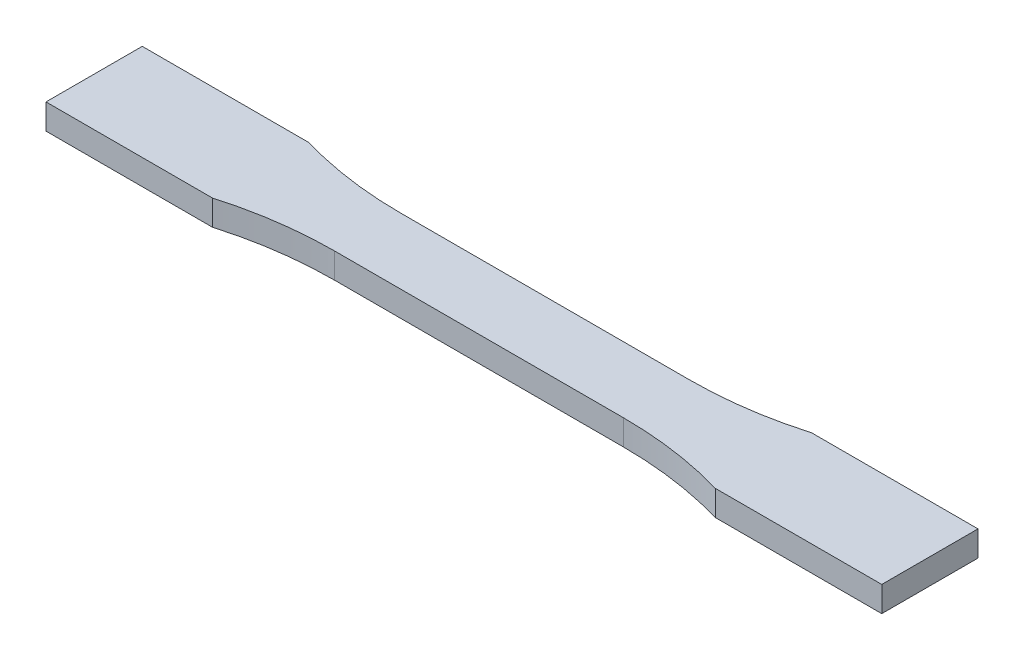
SolidWorks part; units mm, degrees
ref_plane "정면" through (0, 0, 0) normal (0, 0, 1) x (1, 0, 0)
ref_plane "윗면" through (0, 0, 0) normal (0, 1, 0) x (1, 0, 0)
ref_plane "우측면" through (0, 0, 0) normal (1, 0, 0) x (0, 0, -1)
sketch "스케치1" plane through (0, 0, 0) normal (0, 1, 0) x (1, 0, 0)
  line L0 (0, 23.452) -> (0, -24.9244) construction
  line L1 (-28.5, 6.5) -> (28.5, 6.5)
  line L2 (49.6424, -9.5) -> (82.5, -9.5)
  line L3 (49.6424, 9.5) -> (82.5, 9.5)
  line L4 (82.5, 9.5) -> (82.5, -9.5)
  line L5 (-103.6036, 0) -> (120.6466, 0) construction
  line L6 (-82.5, 9.5) -> (-82.5, -9.5)
  line L7 (-49.6424, 9.5) -> (-82.5, 9.5)
  line L8 (82.5, 9.5) -> (82.5, -9.5)
  line L9 (-28.5, -6.5) -> (28.5, -6.5)
  line L10 (-49.6424, -9.5) -> (-82.5, -9.5)
  line L11 (49.6424, -9.5) -> (82.5, -9.5)
  line L14 (49.6424, 9.5) -> (82.5, 9.5)
  line L16 (-49.6424, -9.5) -> (-82.5, -9.5)
  arc A0 (49.6424, 9.5) -> (28.5, 6.5) centre (28.5, 82.5) cw
  arc A1 (-49.6424, 9.5) -> (-28.5, 6.5) centre (-28.5, 82.5) ccw
  arc A2 (49.6424, -9.5) -> (28.5, -6.5) centre (28.5, -82.5) ccw
  arc A3 (-49.6424, -9.5) -> (-28.5, -6.5) centre (-28.5, -82.5) cw
  point P8 (-25, 0)
  point P13 (25, 0)
  point P14 (0, 6.5)
  point P15 (-82.5, 0)
  point P16 (82.5, 0)
  point P20 (0, -6.5)
  dimension "D1" = 165
  dimension "D5" = 152
  dimension "D2" = 19
  dimension "D3" = 13
  dimension "D4" = 57
  dimension "D6" = 50
  dimension "D7" = 25
extrude "보스-돌출1" add sketch "스케치1" along normal mid plane 5 contours L10 A3 L9 A2 L2 L4 L3 A0 L1 A1 L7 L6
sketch "스케치2" plane through (0, 2.5, 0) normal (0, 1, 0) x (1, 0, 0)
  circle A0 centre (0, 0) radius 2.9709
